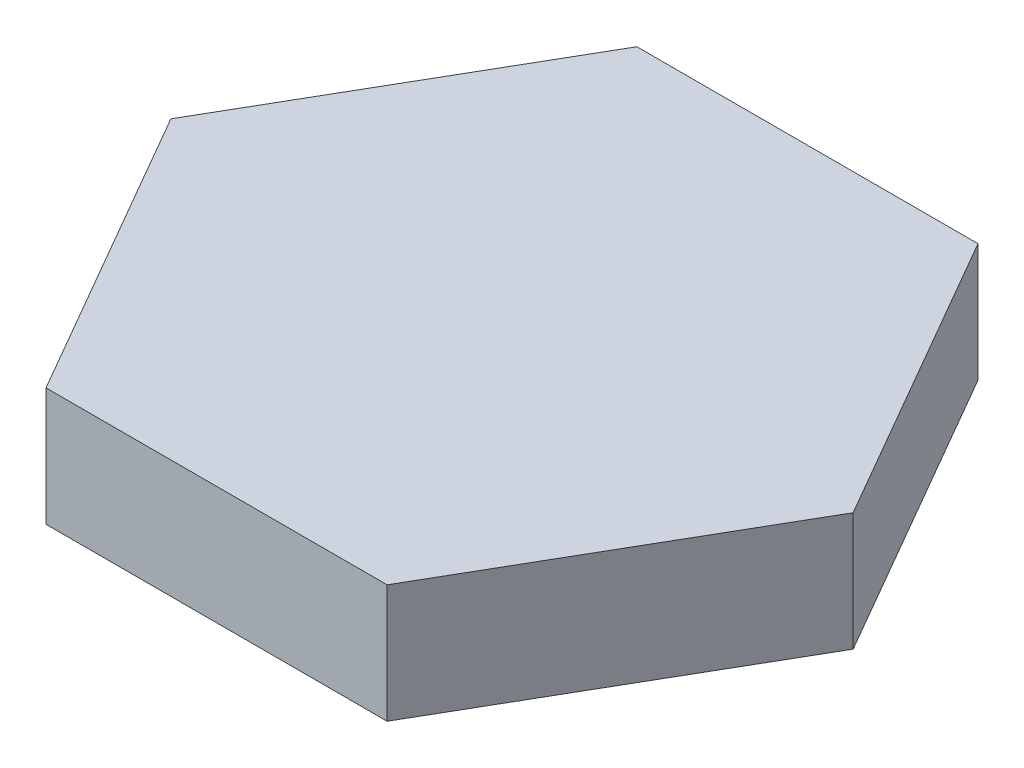
SolidWorks part; units mm, degrees
material "AISI 1020"
ref_plane "Front Plane" through (0, 0, 0) normal (0, 0, 1) x (1, 0, 0)
ref_plane "Top Plane" through (0, 0, 0) normal (0, 1, 0) x (1, 0, 0)
ref_plane "Right Plane" through (0, 0, 0) normal (1, 0, 0) x (0, 0, -1)
sketch "Sketch1" plane through (0, 0, 0) normal (0, 1, 0) x (1, 0, 0)
  line L0 (-43.3013, 25) -> (43.3013, -25) construction
  line L1 (28.8675, 50) -> (-28.8675, 50)
  line L2 (-28.8675, 50) -> (-57.735, 0)
  line L3 (-57.735, 0) -> (-28.8675, -50)
  line L4 (-28.8675, -50) -> (28.8675, -50)
  line L5 (28.8675, -50) -> (57.735, 0)
  line L6 (57.735, 0) -> (28.8675, 50)
  line L7 (0, -50) -> (0, 50) construction
  line L8 (-43.3013, -25) -> (43.3013, 25) construction
  circle A0 centre (0, 0) radius 50 construction
  dimension "D1" = 100
extrude "Boss-Extrude1" add sketch "Sketch1" along normal mid plane 20
sketch "Sketch2" plane through (0, 10, 0) normal (0, 1, 0) x (1, 0, 0)
  line L0 (0, 30) -> (0, -30) construction
  line L1 (-30, 0) -> (30, 0) construction
  circle A0 centre (0, 0) radius 30
  dimension "D1" = 60
